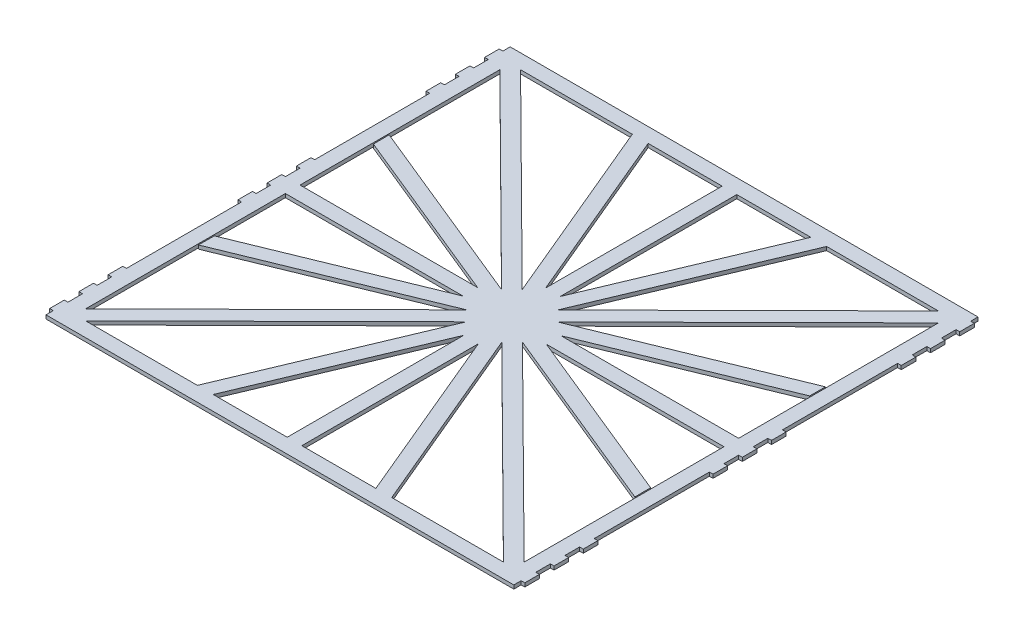
SolidWorks part; units mm, degrees
ref_plane "Front Plane" through (0, 0, 0) normal (0, 0, 1) x (1, 0, 0)
ref_plane "Top Plane" through (0, 0, 0) normal (0, 1, 0) x (1, 0, 0)
ref_plane "Right Plane" through (0, 0, 0) normal (1, 0, 0) x (0, 0, -1)
sketch "Sketch1" plane through (0, 0, 0) normal (0, 1, 0) x (1, 0, 0)
  line L1 (-206.375, -201.6125) -> (206.375, -201.6125)
  line L2 (-206.375, -201.6125) -> (-206.375, 201.6125)
  line L3 (-206.375, 201.6125) -> (206.375, 201.6125)
  line L4 (206.375, -201.6125) -> (206.375, 201.6125)
  line L5 (-206.375, -201.6125) -> (206.375, 201.6125) construction
  line L6 (-206.375, 201.6125) -> (206.375, -201.6125) construction
  point P0 (0, 0)
  dimension "D1" = 412.75
  dimension "D2" = 403.225
extrude "Boss-Extrude1" add sketch "Sketch1" along normal blind 3.175
sketch "Sketch2" plane through (0, 3.175, 0) normal (0, 1, 0) x (1, 0, 0)
  line L0 (-206.375, 201.6125) -> (-206.375, -201.6125) construction
  line L1 (-206.375, 125.4125) -> (-203.2, 125.4125)
  line L2 (-206.375, 125.4125) -> (-206.375, 38.1)
  line L3 (-206.375, 38.1) -> (-203.2, 38.1)
  line L4 (-203.2, 125.4125) -> (-203.2, 38.1)
  line L5 (206.375, 201.6125) -> (-206.375, 201.6125) construction
  line L6 (-206.375, -38.1) -> (-203.2, -38.1)
  line L7 (-206.375, -38.1) -> (-206.375, -125.4125)
  line L8 (-206.375, -125.4125) -> (-203.2, -125.4125)
  line L9 (-203.2, -38.1) -> (-203.2, -125.4125)
  line L10 (-206.375, -201.6125) -> (206.375, -201.6125) construction
  dimension "D1" = 76.2
  dimension "D2" = 3.175
  dimension "D3" = 76.2
  dimension "D4" = 76.2
extrude "Cut-Extrude1" cut sketch "Sketch2" against normal blind 3.175
sketch "Sketch3" plane through (0, 3.175, 0) normal (0, 1, 0) x (1, 0, 0)
  line L0 (-206.375, 201.6125) -> (-206.375, 125.4125) construction
  line L1 (-206.375, 195.2625) -> (-203.2, 195.2625)
  line L2 (-206.375, 195.2625) -> (-206.375, 207.9625)
  line L3 (-206.375, 207.9625) -> (-203.2, 207.9625)
  line L4 (-203.2, 195.2625) -> (-203.2, 207.9625)
  line L18 (-206.375, 169.8625) -> (-206.375, 182.5625)
  line L19 (-206.375, 169.8625) -> (-203.2, 169.8625)
  line L20 (-203.2, 169.8625) -> (-203.2, 182.5625)
  line L21 (-206.375, 182.5625) -> (-203.2, 182.5625)
  line L22 (-206.375, 144.4625) -> (-206.375, 157.1625)
  line L23 (-206.375, 144.4625) -> (-203.2, 144.4625)
  line L24 (-203.2, 144.4625) -> (-203.2, 157.1625)
  line L25 (-206.375, 157.1625) -> (-203.2, 157.1625)
  line L26 (-206.375, 119.0625) -> (-206.375, 131.7625)
  line L27 (-206.375, 119.0625) -> (-203.2, 119.0625)
  line L28 (-203.2, 119.0625) -> (-203.2, 131.7625)
  line L29 (-206.375, 131.7625) -> (-203.2, 131.7625)
  point P20 (-206.375, 201.6125)
  dimension "D1" = 12.7
  dimension "D2" = 3.175
  dimension "D4" = 12.7
  dimension "D3" = 4
extrude "Cut-Extrude2" cut sketch "Sketch3" against normal blind 3.175
sketch "Sketch4" plane through (0, 3.175, 0) normal (0, 1, 0) x (1, 0, 0)
  line L1 (-206.375, 44.45) -> (-203.2, 44.45)
  line L2 (-206.375, 44.45) -> (-206.375, 31.75)
  line L3 (-206.375, 31.75) -> (-203.2, 31.75)
  line L4 (-203.2, 44.45) -> (-203.2, 31.75)
  line L5 (-206.375, 19.05) -> (-206.375, 6.35)
  line L6 (-206.375, 19.05) -> (-203.2, 19.05)
  line L7 (-203.2, 19.05) -> (-203.2, 6.35)
  line L8 (-206.375, 6.35) -> (-203.2, 6.35)
  line L9 (-206.375, -6.35) -> (-206.375, -19.05)
  line L10 (-206.375, -6.35) -> (-203.2, -6.35)
  line L11 (-203.2, -6.35) -> (-203.2, -19.05)
  line L12 (-206.375, -19.05) -> (-203.2, -19.05)
  line L13 (-206.375, -31.75) -> (-206.375, -44.45)
  line L14 (-206.375, -31.75) -> (-203.2, -31.75)
  line L15 (-203.2, -31.75) -> (-203.2, -44.45)
  line L16 (-206.375, -44.45) -> (-203.2, -44.45)
  point P6 (-206.375, 38.1)
  dimension "D1" = 3.175
  dimension "D2" = 12.7
  dimension "D4" = 12.7
  dimension "D3" = 4
extrude "Cut-Extrude3" cut sketch "Sketch4" against normal blind 3.175
mirror "Mirror1" about plane through (0, 0, 0) normal (0, 0, 1) of "Cut-Extrude2"
mirror "Mirror2" about plane through (0, 0, 0) normal (1, 0, 0) of "Cut-Extrude3", "Cut-Extrude2", "Cut-Extrude1", "Mirror1"
sketch "Sketch5" plane through (0, 3.175, 0) normal (0, 1, 0) x (1, 0, 0)
  line L0 (-203.2, 31.75) -> (-203.2, 131.7625) construction
  line L1 (-190.5, 6.35) -> (-6.35, 6.35)
  line L2 (-190.5, 6.35) -> (-190.5, 188.9125)
  line L3 (-190.5, 188.9125) -> (-6.35, 188.9125)
  line L4 (-6.35, 6.35) -> (-6.35, 188.9125)
  line L5 (-190.5, 6.35) -> (-6.35, 188.9125) construction
  line L6 (-190.5, 188.9125) -> (-6.35, 6.35) construction
  line L7 (203.2, 201.6125) -> (-203.2, 201.6125) construction
  line L8 (-190.5, 179.9709) -> (-15.3694, 6.35)
  line L9 (-181.4806, 188.9125) -> (-6.35, 15.2916)
  line L10 (-84.4183, 188.9125) -> (-15.369, 24.2329)
  line L11 (-70.6471, 188.9125) -> (-6.35, 35.5666)
  line L12 (-189.4623, 69.0641) -> (-35.5655, 6.097)
  line L13 (-189.5816, 82.8347) -> (-24.3103, 15.2139)
  line L14 (-189.5816, 82.8347) -> (-189.4623, 69.0641)
  line L15 (-35.5655, 6.097) -> (-15.3694, 6.35)
  line L16 (-24.3103, 15.2139) -> (-15.3694, 6.35)
  line L17 (-84.4183, 188.9125) -> (-70.6471, 188.9125)
  line L18 (-15.369, 24.2329) -> (-6.35, 15.2916)
  line L19 (-6.35, 15.2916) -> (-6.35, 35.5666)
  point P0 (-98.425, 97.6312)
  dimension "D1" = 12.7
  dimension "D2" = 12.7
  dimension "D3" = 6.35
  dimension "D4" = 6.35
  dimension "D5" = 6.35
  dimension "D6" = 12.7
  dimension "D7" = 12.7
  dimension "D8" = 12.7
  dimension "D9" = 22.5
extrude "Cut-Extrude4" cut sketch "Sketch5" against normal blind 3.175 contours L14 L13 L8 L2 L1 L12 | L10 L3 L9 | L3 L11 L4
mirror "Mirror3" about plane through (0, 0, 0) normal (1, 0, 0) of "Cut-Extrude4"
mirror "Mirror4" about plane through (0, 0, 0) normal (0, 0, 1) of "Cut-Extrude4", "Mirror3"
